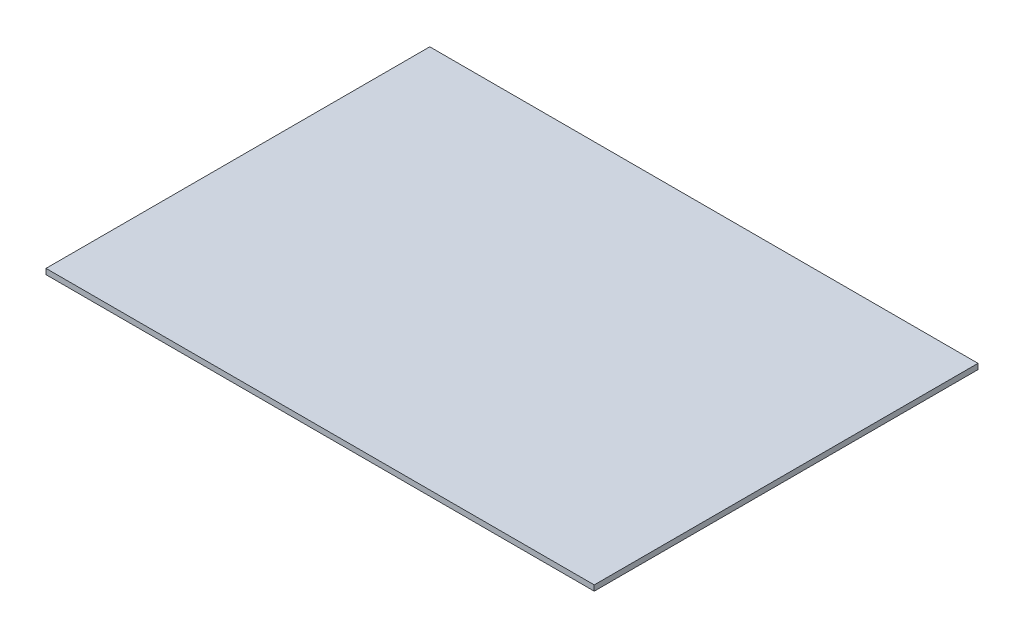
SolidWorks part; units mm, degrees
ref_plane "Front Plane" through (0, 0, 0) normal (0, 0, 1) x (1, 0, 0)
ref_plane "Top Plane" through (0, 0, 0) normal (0, 1, 0) x (1, 0, 0)
ref_plane "Right Plane" through (0, 0, 0) normal (1, 0, 0) x (0, 0, -1)
sketch "Sketch1" plane through (0, 0, 0) normal (0, 1, 0) x (1, 0, 0)
  line L1 (-87.5163, 85.2406) -> (212.4837, 85.2406)
  line L2 (-87.5163, 85.2406) -> (-87.5163, -124.7594)
  line L3 (-87.5163, -124.7594) -> (212.4837, -124.7594)
  line L4 (212.4837, 85.2406) -> (212.4837, -124.7594)
  dimension "D1" = 300
  dimension "D2" = 210
extrude "Boss-Extrude1" add sketch "Sketch1" along normal blind 3 contours L2 L1 L4 L3
